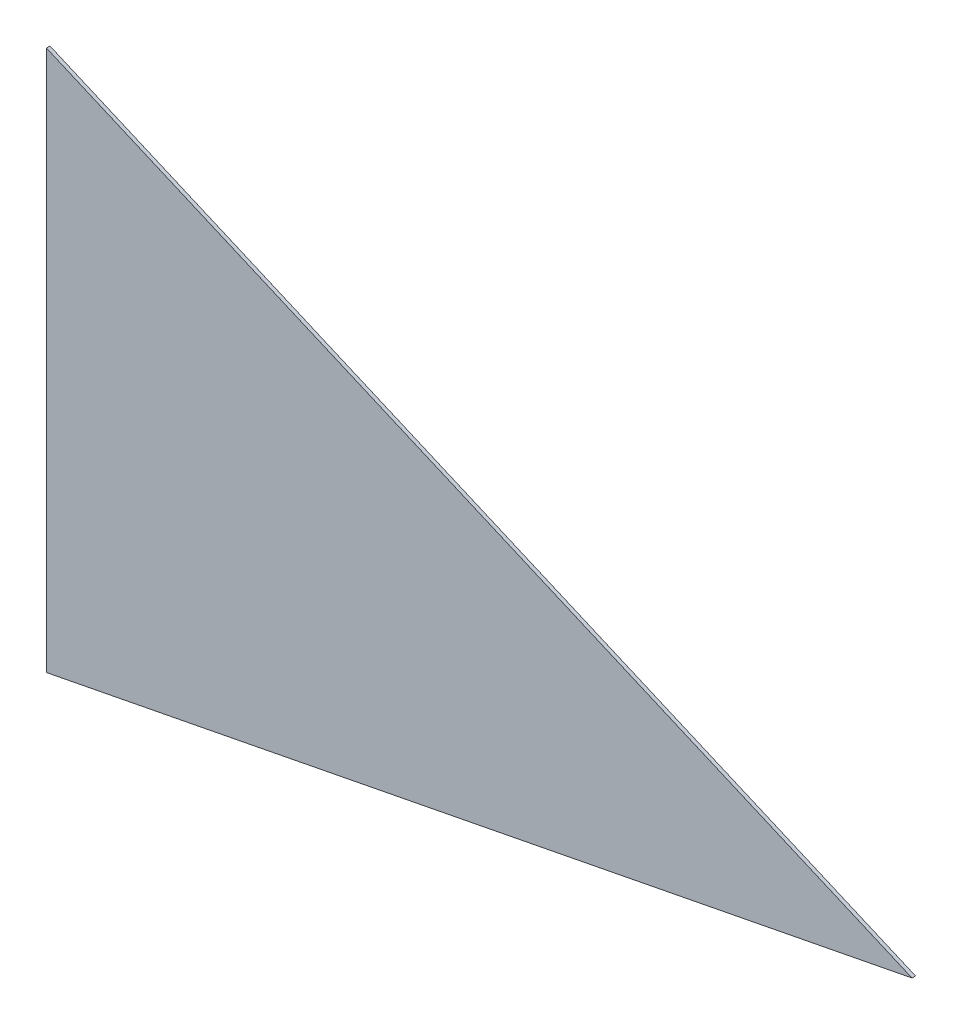
SolidWorks part; units mm, degrees
ref_plane "Plan de face" through (0, 0, 0) normal (0, 0, 1) x (1, 0, 0)
ref_plane "Plan de dessus" through (0, 0, 0) normal (0, 1, 0) x (1, 0, 0)
ref_plane "Plan de droite" through (0, 0, 0) normal (1, 0, 0) x (0, 0, -1)
sketch "Esquisse1" plane through (0, 0, 0) normal (0, 0, 1) x (1, 0, 0)
  line L0 (0, 0) -> (0, 460)
  line L1 (0, 460) -> (750, 0) construction
  line L2 (750, 0) -> (0, 0) construction
  line L3 (0, 0) -> (736.2204, 143.1067)
  line L4 (736.2204, 143.1067) -> (0, 460)
  dimension "D1" = 460
  dimension "D2" = 750
  dimension "D3" = 11
  dimension "D4" = 750
extrude "Boss.-Extru.1" add sketch "Esquisse1" along normal blind 3
